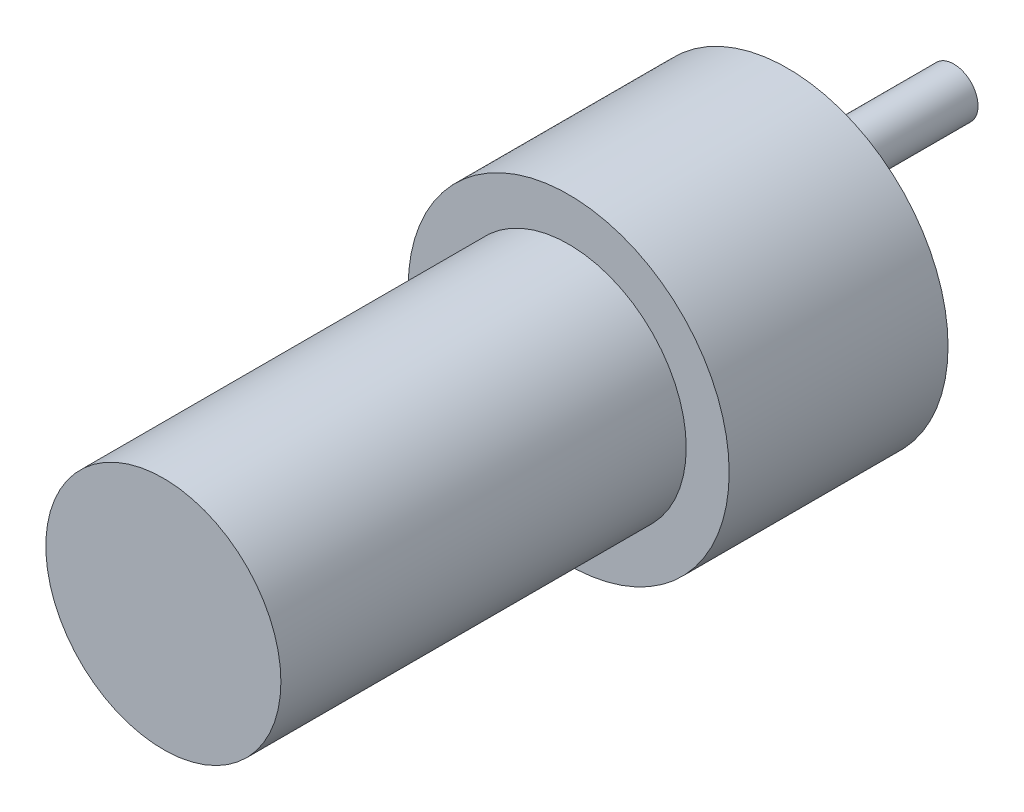
SolidWorks part; units mm, degrees
ref_plane "Front Plane" through (0, 0, 0) normal (0, 0, 1) x (1, 0, 0)
ref_plane "Top Plane" through (0, 0, 0) normal (0, 1, 0) x (1, 0, 0)
ref_plane "Right Plane" through (0, 0, 0) normal (1, 0, 0) x (0, 0, -1)
sketch "Sketch2" plane through (0, 0, 0) normal (0, 0, 1) x (1, 0, 0)
  circle A0 centre (0, 0) radius 19.8
  dimension "D1" = 39.6
extrude "Boss-Extrude1" add sketch "Sketch2" along normal blind 27
sketch "Sketch3" plane through (0, 0, 27) normal (0, 0, 1) x (1, 0, 0)
  circle A0 centre (0, 0) radius 14.5
  dimension "D1" = 29
extrude "Boss-Extrude2" add sketch "Sketch3" along normal blind 50
sketch "Sketch5" plane through (0, 0, 0) normal (0, 0, -1) x (-1, 0, 0)
  circle A0 centre (0, 0) radius 15.5 construction
  circle A1 centre (-15.5, 0) radius 1.6
  circle A2 centre (7.75, 13.4234) radius 1.6
  circle A3 centre (7.75, -13.4234) radius 1.6
  dimension "D1" = 31
  dimension "D3" = 3.2
  dimension "D2" = 120
extrude "Cut-Extrude1" cut sketch "Sketch5" against normal blind 10
sketch "Sketch6" plane through (0, 0, 0) normal (0, 0, -1) x (-1, 0, 0)
  circle A0 centre (0, 7) radius 6
  dimension "D1" = 12
  dimension "D2" = 7
extrude "Boss-Extrude3" add sketch "Sketch6" along normal blind 5.5
sketch "Sketch7" plane through (0, 0, -5.5) normal (0, 0, -1) x (-1, 0, 0)
  circle A0 centre (0, 7) radius 3
  dimension "D1" = 6
extrude "Boss-Extrude4" add sketch "Sketch7" along normal blind 15
